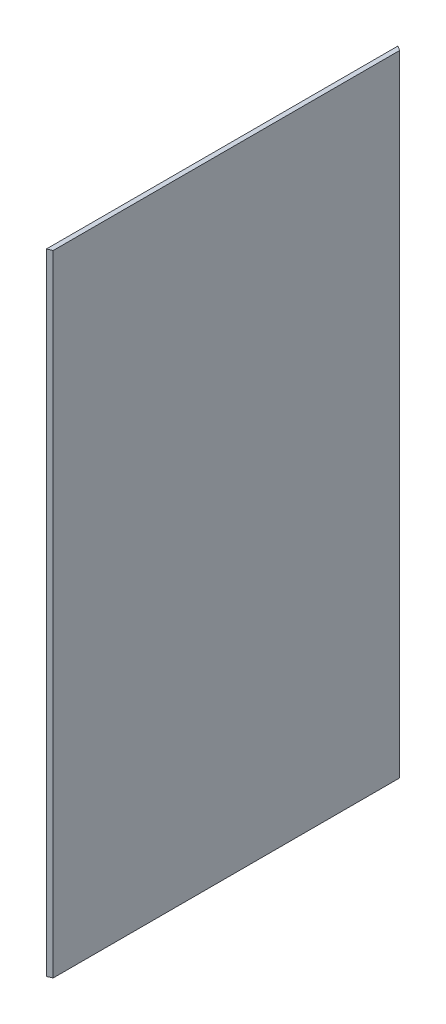
SolidWorks part; units mm, degrees
ref_plane "Спереди" through (0, 0, 0) normal (0, 0, 1) x (1, 0, 0)
ref_plane "Сверху" through (0, 0, 0) normal (0, 1, 0) x (1, 0, 0)
ref_plane "Справа" through (0, 0, 0) normal (1, 0, 0) x (0, 0, -1)
sketch "Эскиз1" plane through (0, 0, 0) normal (0, 1, 0) x (1, 0, 0)
  line L0 (4.0186, 1.7475) -> (79.181, -66.868) construction
  line L1 (0, 0) -> (4, 1.7645)
  line L2 (0, 0) -> (0, 297.3876)
  line L3 (0, 297.3876) -> (4, 294.8273)
  line L4 (4, 1.7645) -> (4, 294.8273)
  dimension "D1" = 4
extrude "Вытянуть1" add sketch "Эскиз1" along normal blind 533
